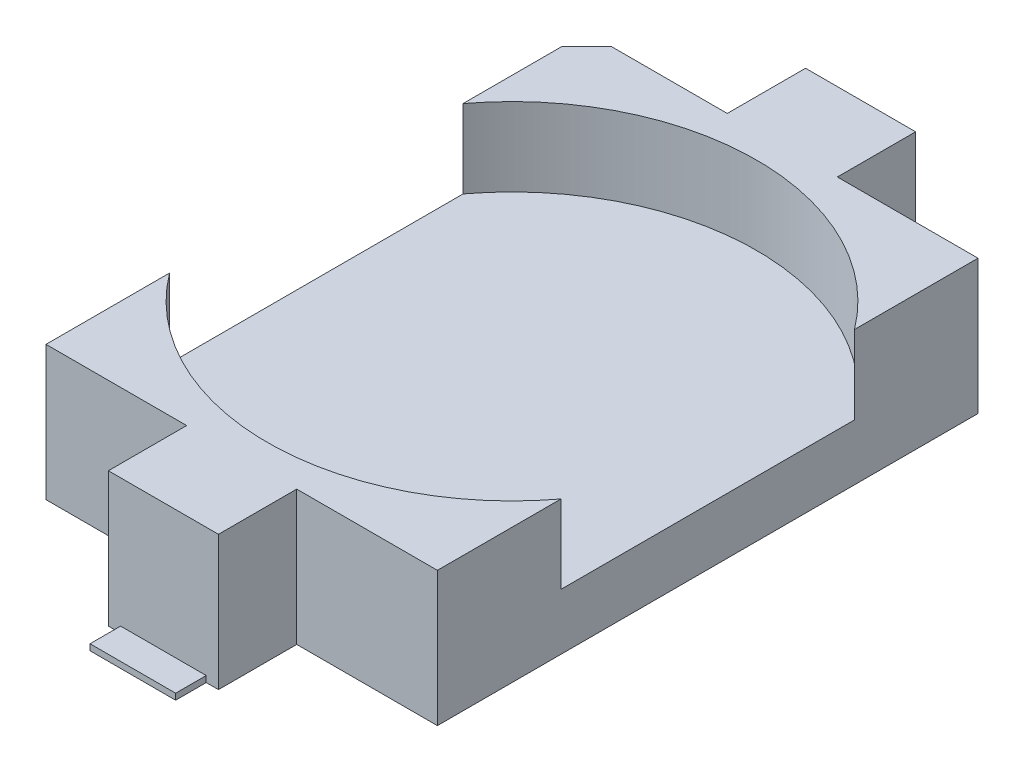
SolidWorks part; units mm, degrees
material "ABS"
ref_plane "Front Plane" through (0, 0, 0) normal (0, 0, 1) x (1, 0, 0)
ref_plane "Top Plane" through (0, 0, 0) normal (0, 1, 0) x (1, 0, 0)
ref_plane "Right Plane" through (0, 0, 0) normal (1, 0, 0) x (0, 0, -1)
sketch "Sketch1" plane through (0, 0, 0) normal (0, 1, 0) x (1, 0, 0)
  line L1 (-8, 11.05) -> (8, 11.05)
  line L2 (-8, 11.05) -> (-8, -11.05)
  line L3 (-8, -11.05) -> (8, -11.05)
  line L4 (8, 11.05) -> (8, -11.05)
  line L5 (-8, 11.05) -> (8, -11.05) construction
  line L6 (-8, -11.05) -> (8, 11.05) construction
  line L7 (-2.25, 14.25) -> (2.25, 14.25)
  line L8 (-2.25, 14.25) -> (-2.25, -14.25)
  line L9 (-2.25, -14.25) -> (2.25, -14.25)
  line L10 (2.25, 14.25) -> (2.25, -14.25)
  line L11 (-2.25, 14.25) -> (2.25, -14.25) construction
  line L12 (-2.25, -14.25) -> (2.25, 14.25) construction
  point P0 (0, 0)
  point P6 (0, 0)
  dimension "D1" = 22.1
  dimension "D2" = 16
  dimension "D3" = 4.5
  dimension "D4" = 28.5
extrude "Boss-Extrude1" add sketch "Sketch1" along normal blind 5.5 contours L8 L1 L2 L3 | L10 L1 L8 L3 | L10 L7 L8 L1 | L10 L3 L8 L9 | L1 L10 L3 L4
sketch "Sketch2" plane through (0, 5.5, 0) normal (0, 1, 0) x (1, 0, 0)
  circle A0 centre (0, 0) radius 10
  dimension "D1" = 20
extrude "Cut-Extrude1" cut sketch "Sketch2" against normal blind 3.2
chamfer "Chamfer1" distance 1 angle 45 1 edges at (-8, 2.75, -11.05)
sketch "Sketch3" plane through (0, 0, 0) normal (0, -1, 0) x (1, 0, 0)
  line L1 (-1.75, 15.5) -> (1.75, 15.5)
  line L2 (-1.75, 15.5) -> (-1.75, -15.5)
  line L3 (-1.75, -15.5) -> (1.75, -15.5)
  line L4 (1.75, 15.5) -> (1.75, -15.5)
  line L5 (-1.75, 15.5) -> (1.75, -15.5) construction
  line L6 (-1.75, -15.5) -> (1.75, 15.5) construction
  point P0 (0, 0)
  dimension "D1" = 3.5
  dimension "D2" = 31
extrude "Boss-Extrude2" add sketch "Sketch3" against normal blind 0.25
